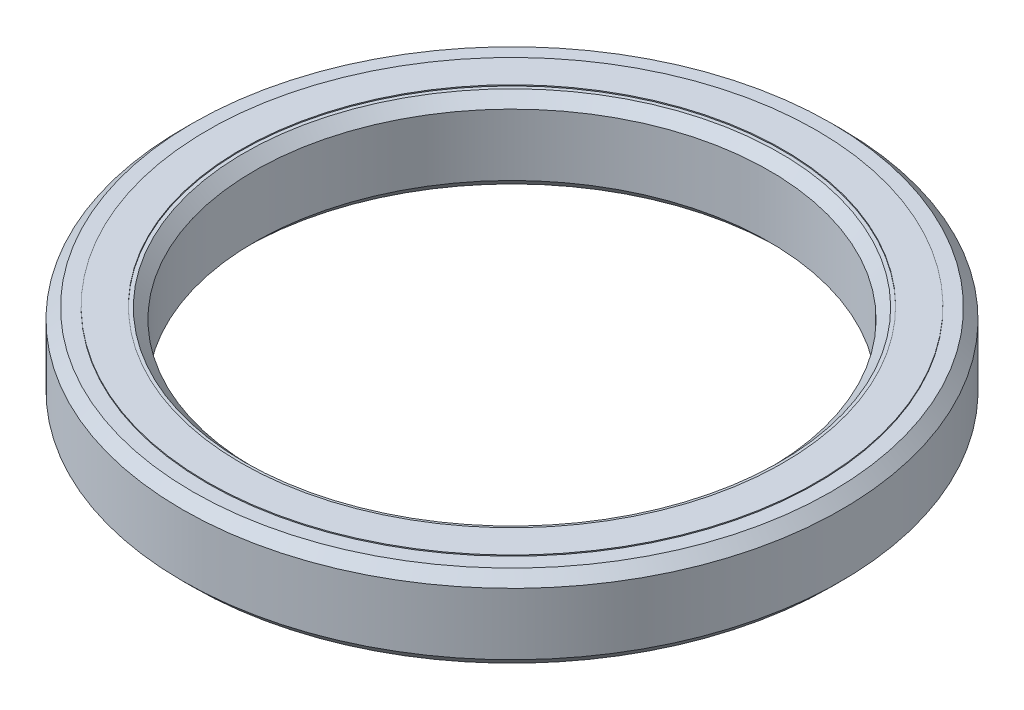
SolidWorks part; units mm, degrees
material "Acero aleado"
ref_plane "Alzado" through (0, 0, 0) normal (0, 0, 1) x (1, 0, 0)
ref_plane "Planta" through (0, 0, 0) normal (0, 1, 0) x (1, 0, 0)
ref_plane "Vista lateral" through (0, 0, 0) normal (1, 0, 0) x (0, 0, -1)
sketch "Croquis1" plane through (0, 0, 0) normal (0, 1, 0) x (1, 0, 0)
  circle A0 centre (0, 0) radius 16
  circle A1 centre (0, 0) radius 12.5
  dimension "D1" = 25
  dimension "D2" = 32
extrude "Saliente-Extruir1" add sketch "Croquis1" along normal mid plane 4
chamfer "Chaflán1" distance 0.5 angle 45 4 edges at (0, -2, 12.5) (0, 2, 12.5) (0, -2, 16) (0, 2, 16)
sketch "Croquis2" plane through (0, 0, 0) normal (0, 1, 0) x (1, 0, 0)
  circle A0 centre (0, 0) radius 13.1697
  circle A1 centre (0, 0) radius 14.7935
extrude "Saliente-Extruir2" add sketch "Croquis2" along normal mid plane 4.1
